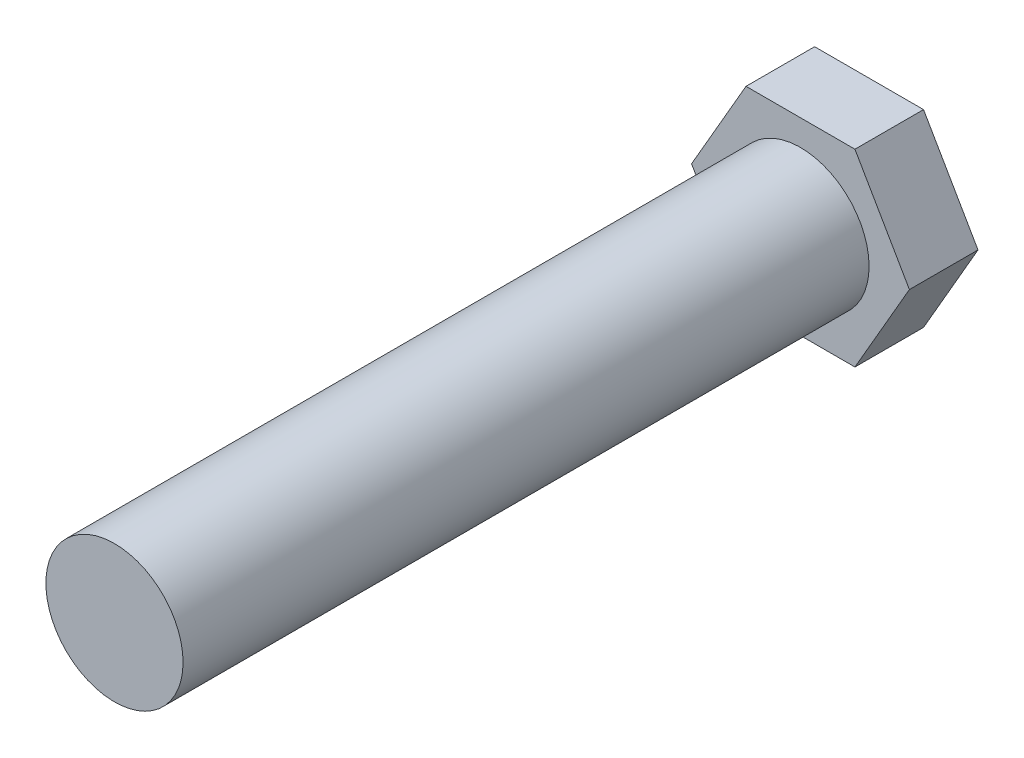
SolidWorks part; units mm, degrees
ref_plane "Front Plane" through (0, 0, 0) normal (0, 0, 1) x (1, 0, 0)
ref_plane "Top Plane" through (0, 0, 0) normal (0, 1, 0) x (1, 0, 0)
ref_plane "Right Plane" through (0, 0, 0) normal (1, 0, 0) x (0, 0, -1)
sketch "Sketch1" plane through (0, 0, 0) normal (0, 0, 1) x (1, 0, 0)
  line L1 (8.0656, 0) -> (4.0328, 6.985)
  line L2 (4.0328, 6.985) -> (-4.0328, 6.985)
  line L3 (-4.0328, 6.985) -> (-8.0656, 0)
  line L4 (-8.0656, 0) -> (-4.0328, -6.985)
  line L5 (-4.0328, -6.985) -> (4.0328, -6.985)
  line L6 (4.0328, -6.985) -> (8.0656, 0)
  circle A0 centre (0, 0) radius 6.985 construction
  dimension "D1" = 13.97
extrude "Boss-Extrude1" add sketch "Sketch1" along normal blind 5.08
sketch "Sketch2" plane through (0, 0, 5.08) normal (0, 0, 1) x (1, 0, 0)
  circle A0 centre (0, 0) radius 5.08
  dimension "D1" = 10.16
extrude "Boss-Extrude2" add sketch "Sketch2" along normal blind 50.8
